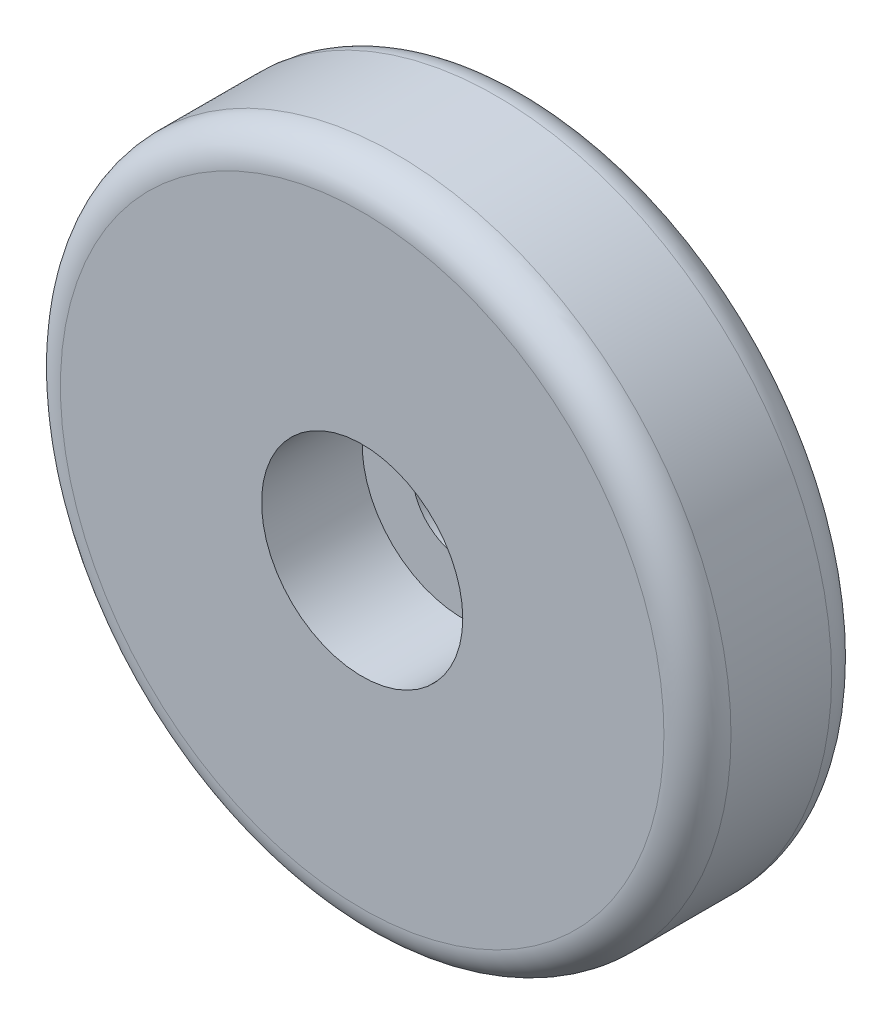
SolidWorks part; units mm, degrees
ref_plane "Plan de face" through (0, 0, 0) normal (0, 0, 1) x (1, 0, 0)
ref_plane "Plan de dessus" through (0, 0, 0) normal (0, 1, 0) x (1, 0, 0)
ref_plane "Plan de droite" through (0, 0, 0) normal (1, 0, 0) x (0, 0, -1)
sketch "Esquisse1" plane through (0, 0, 0) normal (0, 0, 1) x (1, 0, 0)
  circle A0 centre (0, 0) radius 10
  dimension "D1" = 20
extrude "Boss.-Extru.1" add sketch "Esquisse1" along normal blind 5
sketch "Esquisse2" plane through (0, 0, 5) normal (0, 0, 1) x (1, 0, 0)
  circle A0 centre (0, 0) radius 3
  dimension "D1" = 6
extrude "Enlèv. mat.-Extru.1" cut sketch "Esquisse2" against normal blind 3
sketch "Esquisse3" plane through (0, 0, 0) normal (1, 0, 0) x (0, 0, -1)
  line L0 (-2.5, 6.9317) -> (-2.5, -7.9321) construction
  line L1 (-5, 10) -> (-5, -10) construction
  line L2 (0, 10) -> (-5, 10) construction
  line L3 (-5, 10) -> (-5, -10)
  line L4 (0, 10) -> (-5, 10)
  line L5 (0, 10) -> (0, 9)
  arc A0 (-5, 9) -> (-4, 10) centre (-4, 9) cw
  arc A1 (0, 9) -> (-1, 10) centre (-1, 9) ccw
  dimension "D1" = 1
revolve "Enlèvement de matière-Révolution1" cut sketch "Esquisse3" angle 360 about axis through (0, 0, 5) along (0, 0, -1)
sketch "Esquisse9" plane through (0, 0, 0) normal (0, 0, -1) x (-1, 0, 0)
  circle A0 centre (0, 0) radius 1.5
  dimension "D1" = 3
extrude "Enlèv. mat.-Extru.2" cut sketch "Esquisse9" against normal blind 3
